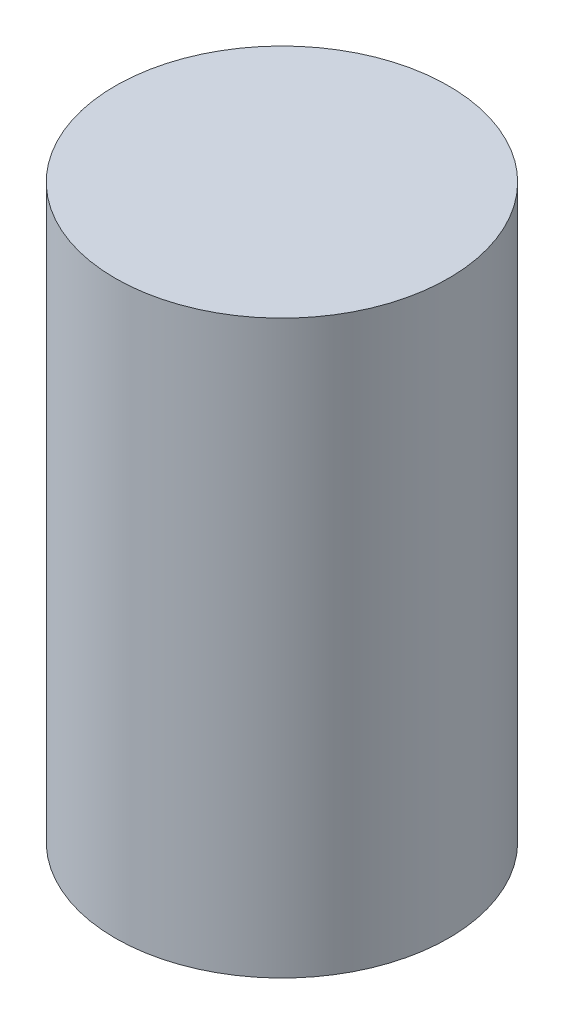
SolidWorks part; units mm, degrees
ref_plane "Спереди" through (0, 0, 0) normal (0, 0, 1) x (1, 0, 0)
ref_plane "Сверху" through (0, 0, 0) normal (0, 1, 0) x (1, 0, 0)
ref_plane "Справа" through (0, 0, 0) normal (1, 0, 0) x (0, 0, -1)
sketch "Эскиз1" plane through (0, 0, 0) normal (0, 1, 0) x (1, 0, 0)
  circle A0 centre (0, 0) radius 3500
  dimension "D1" = 7000
extrude "Бобышка-Вытянуть1" add sketch "Эскиз1" along normal blind 12000
